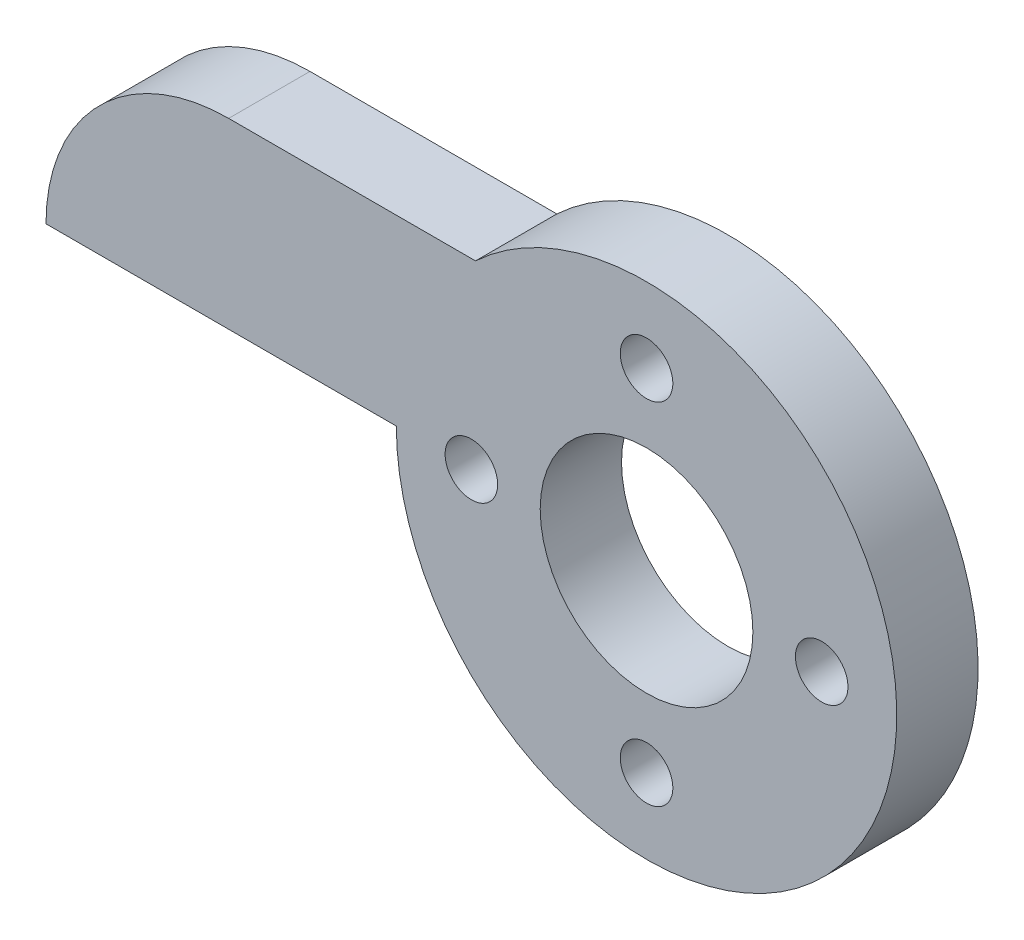
SolidWorks part; units mm, degrees
ref_plane "Front Plane" through (0, 0, 0) normal (0, 0, 1) x (1, 0, 0)
ref_plane "Top Plane" through (0, 0, 0) normal (0, 1, 0) x (1, 0, 0)
ref_plane "Right Plane" through (0, 0, 0) normal (1, 0, 0) x (0, 0, -1)
sketch "Sketch2" plane through (0, 0, 0) normal (0, 0, 1) x (1, 0, 0)
  line L0 (0, -7) -> (0, 7) construction
  line L1 (-7, 0) -> (7, 0) construction
  line L2 (-10, 0) -> (-24, 0)
  line L3 (-16.7, 7.3) -> (-6.8345, 7.3)
  circle A0 centre (0, 0) radius 4.25
  circle A1 centre (0, 0) radius 10
  circle A2 centre (7, 0) radius 1.05
  circle A3 centre (0, 7) radius 1.05
  circle A4 centre (-7, 0) radius 1.05
  circle A5 centre (0, -7) radius 1.05
  arc A6 (-24, 0) -> (-16.7, 7.3) centre (-16.7, 0) cw
  point P7 (0, 0)
  point P10 (0, 0)
  point P18 (-31.4514, 0)
  dimension "D1" = 20
  dimension "D2" = 8.5
  dimension "D4" = 2.1
  dimension "D3" = 14
  dimension "D5" = 7.3
  dimension "D6" = 14
extrude "Boss-Extrude2" add sketch "Sketch2" along normal blind 3.25 contours A6 L2 A1 L3 | A1 A5 A4 A3 A2 A0
sketch "Sketch3" plane through (0, 0, 0) normal (0, 0, -1) x (-1, 0, 0)
  line L0 (14.5235, 7.3) -> (14.5235, 0)
  line L1 (16.7, 7.3) -> (6.8345, 7.3) construction
  line L2 (10, 0) -> (24, 0) construction
  dimension "D1" = 9.4765
